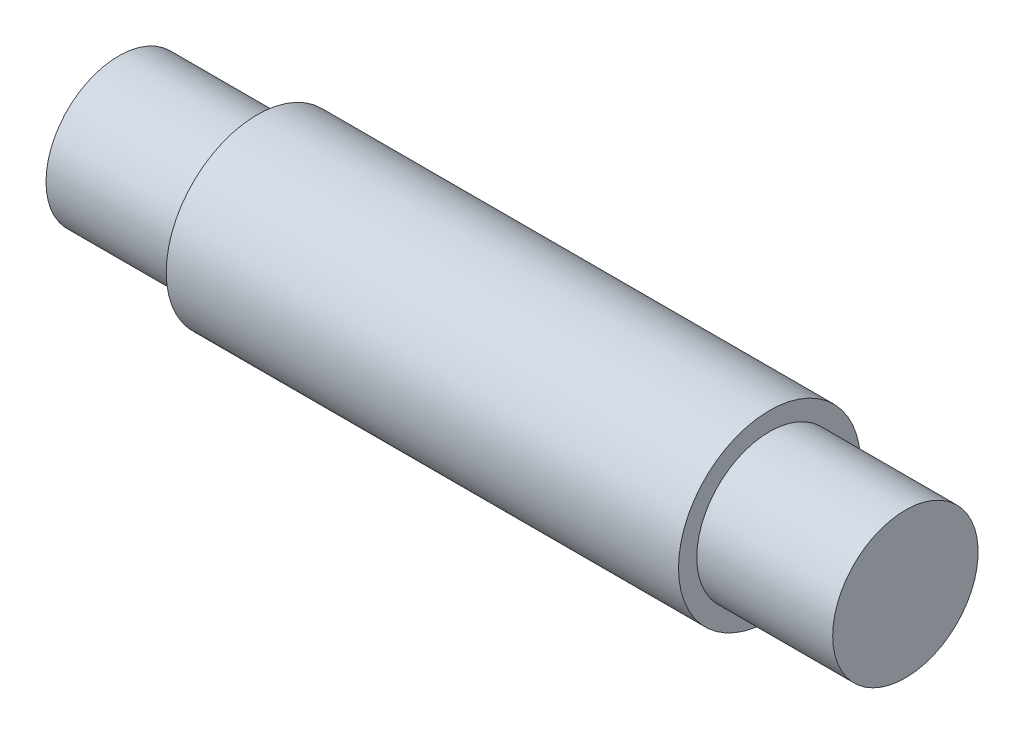
SolidWorks part; units mm, degrees
material "AISI 304"
ref_plane "Front Plane" through (0, 0, 0) normal (0, 0, 1) x (1, 0, 0)
ref_plane "Top Plane" through (0, 0, 0) normal (0, 1, 0) x (1, 0, 0)
ref_plane "Right Plane" through (0, 0, 0) normal (1, 0, 0) x (0, 0, -1)
sketch "Croquis1" plane through (0, 0, 0) normal (0, 0, 1) x (1, 0, 0)
  line L2 (-43, 7.95) -> (-27.8578, 7.95)
  line L3 (-27.8578, 7.95) -> (-27.8578, 9.95)
  line L4 (-27.8578, 9.95) -> (28.1422, 9.95)
  line L5 (28.1422, 9.95) -> (28.1422, 7.95)
  line L6 (28.1422, 7.95) -> (43, 7.95)
  line L8 (-43, 0) -> (66.1016, 0) construction
  line L9 (-43, 7.95) -> (-43, 0)
  line L10 (43, 7.95) -> (43, 0)
  line L11 (-43, 0) -> (43, 0)
  point P4 (0, 0)
  dimension "D1" = 86
  dimension "D2" = 56
  dimension "D3" = 15.9
  dimension "D4" = 15.9
  dimension "D5" = 19.9
revolve "Revolución1" add sketch "Croquis1" angle 360 about L8
